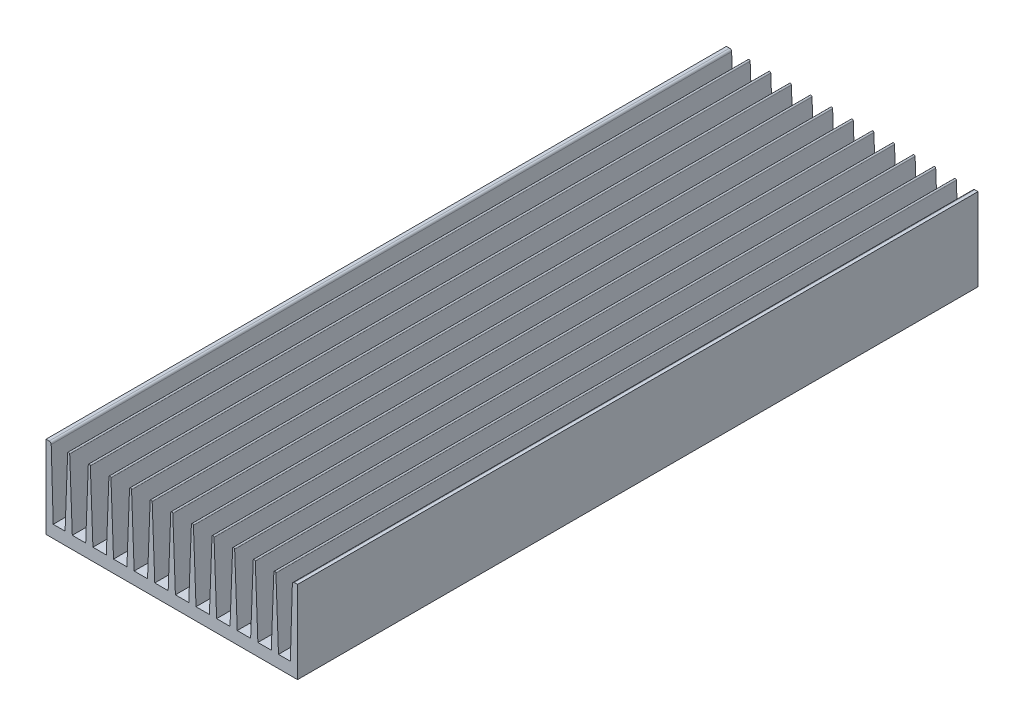
SolidWorks part; units mm, degrees
ref_plane "Спереди" through (0, 0, 0) normal (0, 0, 1) x (1, 0, 0)
ref_plane "Сверху" through (0, 0, 0) normal (0, 1, 0) x (1, 0, 0)
ref_plane "Справа" through (0, 0, 0) normal (1, 0, 0) x (0, 0, -1)
sketch "Эскиз1" plane through (0, 0, 0) normal (0, 0, 1) x (1, 0, 0)
  line L0 (0, 40) -> (1.529, 40)
  line L1 (0, 0) -> (122, 0)
  line L2 (2.5285, 39.0294) -> (3.5, 6)
  line L3 (0, 40) -> (0, 0)
  line L4 (122, 40) -> (122, 0)
  line L5 (61, 63.7127) -> (61, -22.2582) construction
  line L8 (122, 40) -> (120.471, 40)
  line L9 (119.4715, 39.0294) -> (118.5, 6)
  line L10 (3.5, 6) -> (118.5, 6)
  arc A0 (1.529, 40) -> (2.5285, 39.0294) centre (1.529, 39) cw
  arc A2 (120.471, 40) -> (119.4715, 39.0294) centre (120.471, 39) ccw
  point P18 (119.5, 40)
  dimension "D9" = 1
  dimension "D1" = 122
  dimension "D2" = 6
  dimension "D3" = 40
  dimension "D4" = 3.5
  dimension "D7" = 2.5
extrude "Вытянуть1" add sketch "Эскиз1" along normal blind 330
sketch "Эскиз2" plane through (0, 0, 330) normal (0, 0, 1) x (1, 0, 0)
  line L0 (118.5, 6) -> (3.5, 6) construction
  line L1 (10.5, 39.5) -> (9.25, 6)
  line L2 (11, 39.5) -> (11, 22.5548) construction
  line L3 (11.5, 39.5) -> (12.75, 6)
  line L4 (9.25, 6) -> (12.75, 6)
  line L6 (0, 40) -> (0, 0) construction
  arc A0 (10.5, 39.5) -> (11.5, 39.5) centre (11, 39.5) cw
  dimension "D1" = 34
  dimension "D3" = 0.5
  dimension "D2" = 3.5
  dimension "D4" = 11
  dimension "D5" = 1
extrude "Вытянуть3" add sketch "Эскиз2" against normal blind 330
pattern_curve "Кривая1" of "Вытянуть3" along edge at (61, 0, 0) parameters "D1"=11, "D3"=10, "D2"=1, "D4"=50
sketch "Эскиз3" plane through (0, 0, 0) normal (0, -1, 0) x (1, 0, 0)
  line L0 (-14.0506, 322) -> (137.5079, 322) construction
  line L1 (0, 330) -> (122, 330) construction
  line L2 (0, 330) -> (0, 0) construction
  line L3 (-46.7511, 165) -> (151.4312, 165) construction
  line L4 (0, 0) -> (122, 0) construction
  circle A0 centre (28, 322) radius 2.25
  circle A1 centre (94, 322) radius 2.25
  circle A2 centre (94, 8) radius 2.25
  circle A3 centre (28, 8) radius 2.25
  dimension "D2" = 66
  dimension "D4" = 4.5
  dimension "D1" = 8
  dimension "D3" = 28
extrude "Вырез-Вытянуть1" cut sketch "Эскиз3" against normal blind 6
sketch "Эскиз4" plane through (147.9336, 0, 237.9463) normal (0, -1, 0) x (-1, 0, 0)
  line L0 (68.9336, 91.9463) -> (68.9336, 211.9463) construction
  line L1 (94.9336, -66.7149) -> (94.9336, 39.2256) construction
  line L2 (116.9336, 171.9463) -> (116.9336, 111.9463) construction
  line L3 (147.9336, 237.9463) -> (25.9336, 237.9463) construction
  line L5 (116.9336, 111.9463) -> (81.9336, 111.9463) construction
  line L6 (116.9336, 171.9463) -> (81.9336, 171.9463) construction
  line L7 (81.9336, 171.9463) -> (81.9336, 111.9463) construction
  line L8 (147.9336, -92.0537) -> (147.9336, 237.9463) construction
  line L9 (147.9336, -92.0537) -> (25.9336, -92.0537) construction
  circle A0 centre (94.9336, -51.0537) radius 1.6
  circle A1 centre (116.9336, 111.9463) radius 1.6
  circle A2 centre (68.9336, 211.9463) radius 1.6
  circle A3 centre (68.9336, 91.9463) radius 1.6
  circle A4 centre (81.9336, 111.9463) radius 1.6
  circle A5 centre (116.9336, 171.9463) radius 1.6
  circle A6 centre (81.9336, 171.9463) radius 1.6
  circle A7 centre (94.9336, 58.9463) radius 1.6
  circle A8 centre (55.9336, -65.5537) radius 1.6
  circle A9 centre (67.9336, 72.4463) radius 1.6
  dimension "D3" = 110
  dimension "D5" = 120
  dimension "D6" = 3.2
  dimension "D7" = 35
  dimension "D8" = 60
  dimension "D10" = 3.2
  dimension "D11" = 126
  dimension "D12" = 53
  dimension "D13" = 41
  dimension "D14" = 26.5
  dimension "D15" = 164.5
  dimension "D2" = 79
  dimension "D4" = 26
  dimension "D9" = 31
  dimension "D16" = 80
  dimension "D17" = 92
extrude "Вырез-Вытянуть2" cut sketch "Эскиз4" against normal blind 6
cosmetic thread "Условное изображение резьбы5" parameters "D2"=4
cosmetic thread "Условное изображение резьбы7" parameters "D2"=4
cosmetic thread "Условное изображение резьбы8"
cosmetic thread "Условное изображение резьбы9"
cosmetic thread "Условное изображение резьбы10"
cosmetic thread "Условное изображение резьбы11"
cosmetic thread "Условное изображение резьбы12"
cosmetic thread "Условное изображение резьбы13"
cosmetic thread "Условное изображение резьбы14"
cosmetic thread "Условное изображение резьбы15"
